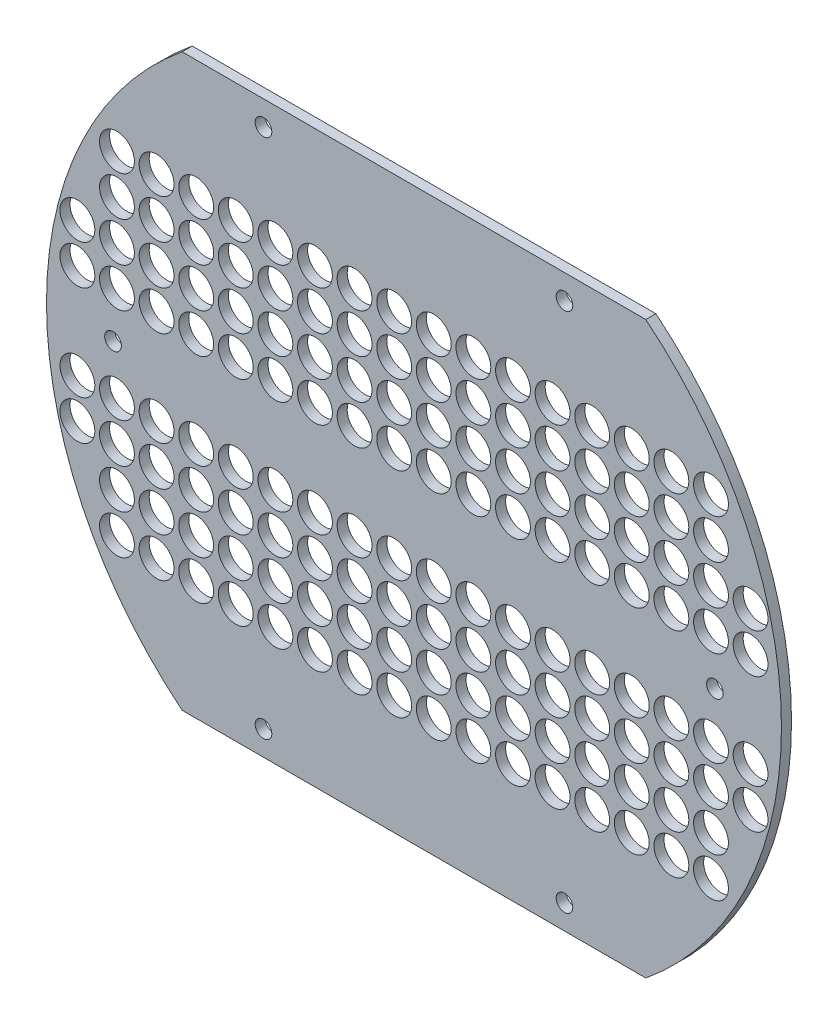
SolidWorks part; units mm, degrees
ref_plane "Front Plane" through (0, 0, 0) normal (0, 0, 1) x (1, 0, 0)
ref_plane "Top Plane" through (0, 0, 0) normal (0, 1, 0) x (1, 0, 0)
ref_plane "Right Plane" through (0, 0, 0) normal (1, 0, 0) x (0, 0, -1)
sketch "Sketch1" plane through (0, 0, 0) normal (0, 0, 1) x (1, 0, 0)
  line L1 (-146.3694, 180) -> (146.3694, 180)
  line L2 (-146.3694, -180) -> (146.3694, -180)
  arc A0 (-146.3694, 180) -> (-146.3694, -180) centre (0, 0) ccw
  arc A1 (146.3694, -180) -> (146.3694, 180) centre (0, 0) ccw
  dimension "D1" = 464
  dimension "D2" = 180
  dimension "D3" = 180
extrude "Boss-Extrude1" add sketch "Sketch1" along normal blind 6.35
sketch "Sketch2" plane through (0, 0, 6.35) normal (0, 0, 1) x (1, 0, 0)
  circle A1 centre (-190, 0) radius 5.25
  circle A7 centre (-95, 164.5448) radius 5.25
  circle A8 centre (95, 164.5448) radius 5.25
  circle A9 centre (190, 0) radius 5.25
  circle A15 centre (95, -164.5448) radius 5.25
  circle A16 centre (-95, -164.5448) radius 5.25
  point P16 (0, 0)
  dimension "D1" = 190
  dimension "D2" = 10.5
  dimension "D3" = 6
extrude "Cut-Extrude1" cut sketch "Sketch2" against normal through all
sketch "Sketch3" plane through (0, 0, 6.35) normal (0, 0, 1) x (1, 0, 0)
  line L0 (0, 140.2547) -> (0, -298.7075) construction
  line L1 (-353.8302, 0) -> (406.1509, 0) construction
  circle A0 centre (12.5, -30) radius 11
  circle A1 centre (12.5, -55) radius 11
  circle A2 centre (12.5, -80) radius 11
  circle A3 centre (12.5, -105) radius 11
  circle A4 centre (37.5, -30) radius 11
  circle A5 centre (37.5, -55) radius 11
  circle A6 centre (62.5, -30) radius 11
  circle A7 centre (62.5, -55) radius 11
  circle A8 centre (87.5, -30) radius 11
  circle A9 centre (87.5, -55) radius 11
  circle A10 centre (112.5, -30) radius 11
  circle A11 centre (112.5, -55) radius 11
  circle A12 centre (137.5, -30) radius 11
  circle A13 centre (137.5, -55) radius 11
  circle A14 centre (162.5, -30) radius 11
  circle A15 centre (162.5, -55) radius 11
  circle A16 centre (187.5, -30) radius 11
  circle A17 centre (187.5, -55) radius 11
  circle A18 centre (212.5, -30) radius 11
  circle A19 centre (212.5, -55) radius 11
  circle A20 centre (37.5, -80) radius 11
  circle A21 centre (37.5, -105) radius 11
  circle A22 centre (62.5, -80) radius 11
  circle A23 centre (62.5, -105) radius 11
  circle A24 centre (87.5, -80) radius 11
  circle A25 centre (87.5, -105) radius 11
  circle A26 centre (112.5, -80) radius 11
  circle A27 centre (112.5, -105) radius 11
  circle A28 centre (137.5, -80) radius 11
  circle A29 centre (137.5, -105) radius 11
  circle A30 centre (162.5, -80) radius 11
  circle A31 centre (162.5, -105) radius 11
  circle A32 centre (187.5, -80) radius 11
  circle A33 centre (187.5, -105) radius 11
  dimension "D1" = 22
  dimension "D2" = 22
  dimension "D3" = 22
  dimension "D4" = 22
  dimension "D5" = 12.5
  dimension "D6" = 30
  dimension "D7" = 55
  dimension "D8" = 80
  dimension "D9" = 105
  dimension "D12" = 37.5
  dimension "D13" = 37.5
  dimension "D10" = 9
  dimension "D11" = 8
extrude "Cut-Extrude2" cut sketch "Sketch3" against normal through all
mirror "Mirror2" about plane through (0, 0, 0) normal (0, 1, 0) of "Cut-Extrude2" second plane through (0, 0, 0) second plane normal (1, 0, 0)
